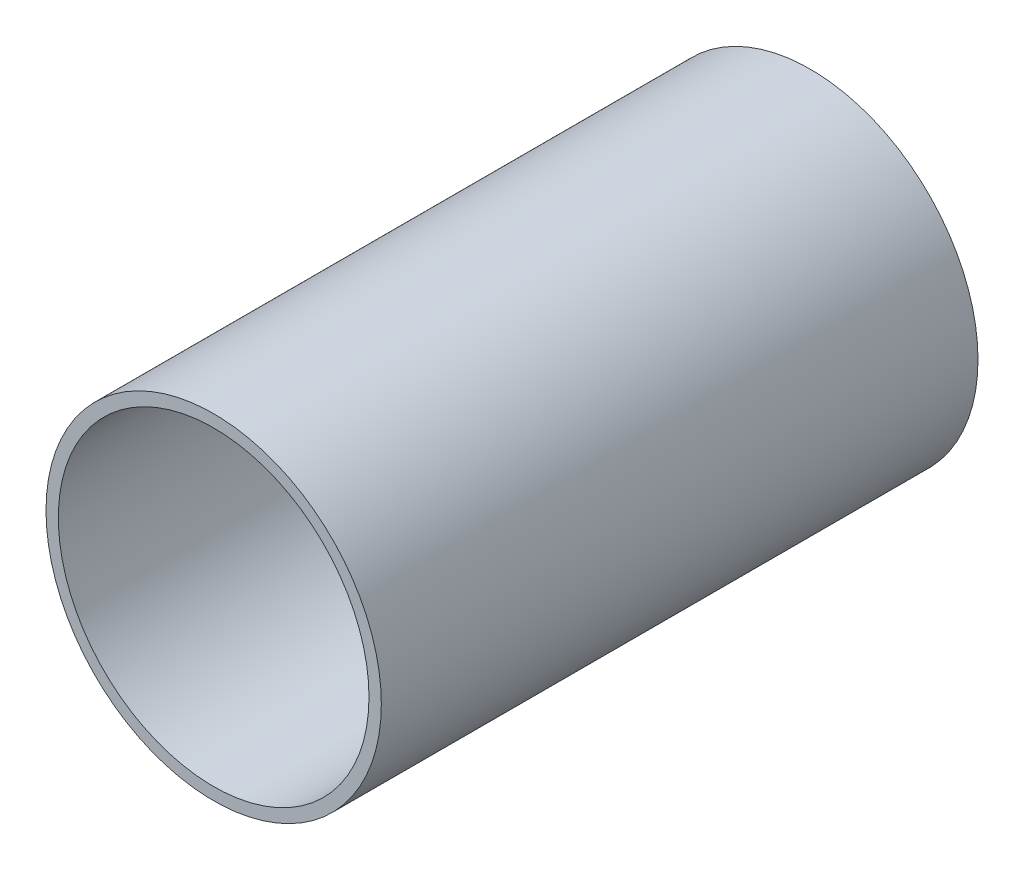
SolidWorks part; units mm, degrees
ref_plane "Front Plane" through (0, 0, 0) normal (1, 0, 0) x (0, 1, 0)
ref_plane "Top Plane" through (0, 0, 0) normal (0, 0, 1) x (0, 1, 0)
ref_plane "Right Plane" through (0, 0, 0) normal (0, 1, 0) x (-1, 0, 0)
sketch "Sketch1" plane through (0, 0, 0) normal (0, 1, 0) x (-1, 0, 0)
  line L0 (19.5, 0) -> (19.25, 8)
  line L1 (19.25, 8) -> (16.5, 9.5)
  line L2 (16.5, 9.5) -> (16.5, 20)
  line L3 (16.5, 20) -> (0, 20) construction
  line L4 (0, 20) -> (0, 0) construction
  line L5 (0, 0) -> (19.5, 0) construction
  line L8 (68, 0) -> (19.5, 0)
  line L9 (68, 0) -> (68, 2)
  line L10 (68, 2) -> (22, 2)
  line L11 (22, 2) -> (19.5, 20)
  line L12 (19.5, 20) -> (16.5, 20)
  dimension "D1" = 19.5
  dimension "D2" = 8
  dimension "D3" = 19.25
  dimension "D4" = 16.5
  dimension "D5" = 9.5
  dimension "D6" = 20
  dimension "D7" = 16.5
  dimension "D9" = 2
  dimension "D10" = 22
  dimension "D11" = 19.5
  dimension "D12" = 68
revolve "Revolve1" add sketch "Sketch1" angle 360 about L4
sketch "ring-1mm" plane through (0, 0, 2) normal (0, 0, 1) x (1, 0, 0)
  circle A0 centre (0, 0) radius 63
  circle A1 centre (0, 0) radius 68
  circle A2 centre (0, 0) radius 68
  dimension "D1" = 0
  dimension "D2" = 5
extrude "Boss-Extrude1" add sketch "ring-1mm" along normal blind 240
sketch "Sketch3-base-openings" plane through (0, 0, 2) normal (0, 0, 1) x (1, 0, 0)
  line L0 (0, 0) -> (63, 0) construction
  line L1 (0, 0) -> (62.0429, 10.9398) construction
  line L4 (29.0954, 5.1303) -> (48.4923, 8.5505)
  line L5 (29.0954, -5.1303) -> (48.4923, -8.5505)
  line L6 (27.7625, -10.1047) -> (46.2708, -16.8412)
  line L7 (22.6322, -18.9907) -> (37.7203, -31.6511)
  line L8 (18.9907, -22.6322) -> (31.6511, -37.7203)
  line L9 (10.1047, -27.7625) -> (16.8412, -46.2708)
  line L10 (5.1303, -29.0954) -> (8.5505, -48.4923)
  line L11 (-5.1303, -29.0954) -> (-8.5505, -48.4923)
  line L12 (-10.1047, -27.7625) -> (-16.8412, -46.2708)
  line L13 (-18.9907, -22.6322) -> (-31.6511, -37.7203)
  line L14 (-22.6322, -18.9907) -> (-37.7203, -31.6511)
  line L15 (-27.7625, -10.1047) -> (-46.2708, -16.8412)
  line L16 (-29.0954, -5.1303) -> (-48.4923, -8.5505)
  line L17 (-29.0954, 5.1303) -> (-48.4923, 8.5505)
  line L18 (-27.7625, 10.1047) -> (-46.2708, 16.8412)
  line L19 (-22.6322, 18.9907) -> (-37.7203, 31.6511)
  line L20 (-18.9907, 22.6322) -> (-31.6511, 37.7203)
  line L21 (-10.1047, 27.7625) -> (-16.8412, 46.2708)
  line L22 (-5.1303, 29.0954) -> (-8.5505, 48.4923)
  line L23 (5.1303, 29.0954) -> (8.5505, 48.4923)
  line L24 (10.1047, 27.7625) -> (16.8412, 46.2708)
  line L25 (18.9907, 22.6322) -> (31.6511, 37.7203)
  line L26 (22.6322, 18.9907) -> (37.7203, 31.6511)
  line L27 (27.7625, 10.1047) -> (46.2708, 16.8412)
  circle A0 centre (0, 0) radius 63 construction
  arc A3 (29.0954, 5.1303) -> (29.0954, -5.1303) centre (30, 0) ccw
  arc A4 (48.4923, -8.5505) -> (48.4923, 8.5505) centre (50, 0) ccw
  circle A5 centre (0, 0) radius 63 construction
  arc A6 (27.7625, -10.1047) -> (22.6322, -18.9907) centre (25.9808, -15) ccw
  arc A7 (37.7203, -31.6511) -> (46.2708, -16.8412) centre (43.3013, -25) ccw
  arc A8 (18.9907, -22.6322) -> (10.1047, -27.7625) centre (15, -25.9808) ccw
  arc A9 (16.8412, -46.2708) -> (31.6511, -37.7203) centre (25, -43.3013) ccw
  arc A10 (5.1303, -29.0954) -> (-5.1303, -29.0954) centre (0, -30) ccw
  arc A11 (-8.5505, -48.4923) -> (8.5505, -48.4923) centre (0, -50) ccw
  arc A12 (-10.1047, -27.7625) -> (-18.9907, -22.6322) centre (-15, -25.9808) ccw
  arc A13 (-31.6511, -37.7203) -> (-16.8412, -46.2708) centre (-25, -43.3013) ccw
  arc A14 (-22.6322, -18.9907) -> (-27.7625, -10.1047) centre (-25.9808, -15) ccw
  arc A15 (-46.2708, -16.8412) -> (-37.7203, -31.6511) centre (-43.3013, -25) ccw
  arc A16 (-29.0954, -5.1303) -> (-29.0954, 5.1303) centre (-30, 0) ccw
  arc A17 (-48.4923, 8.5505) -> (-48.4923, -8.5505) centre (-50, 0) ccw
  arc A18 (-27.7625, 10.1047) -> (-22.6322, 18.9907) centre (-25.9808, 15) ccw
  arc A19 (-37.7203, 31.6511) -> (-46.2708, 16.8412) centre (-43.3013, 25) ccw
  arc A20 (-18.9907, 22.6322) -> (-10.1047, 27.7625) centre (-15, 25.9808) ccw
  arc A21 (-16.8412, 46.2708) -> (-31.6511, 37.7203) centre (-25, 43.3013) ccw
  arc A22 (-5.1303, 29.0954) -> (5.1303, 29.0954) centre (0, 30) ccw
  arc A23 (8.5505, 48.4923) -> (-8.5505, 48.4923) centre (0, 50) ccw
  arc A24 (10.1047, 27.7625) -> (18.9907, 22.6322) centre (15, 25.9808) ccw
  arc A25 (31.6511, 37.7203) -> (16.8412, 46.2708) centre (25, 43.3013) ccw
  arc A26 (22.6322, 18.9907) -> (27.7625, 10.1047) centre (25.9808, 15) ccw
  arc A27 (46.2708, 16.8412) -> (37.7203, 31.6511) centre (43.3013, 25) ccw
  point P84 (0, 0)
  dimension "D2" = 30
  dimension "D1" = 10
  dimension "D3" = 20
  dimension "D4" = 12
extrude "Cut-Extrude2" cut sketch "Sketch3-base-openings" against normal blind 240
